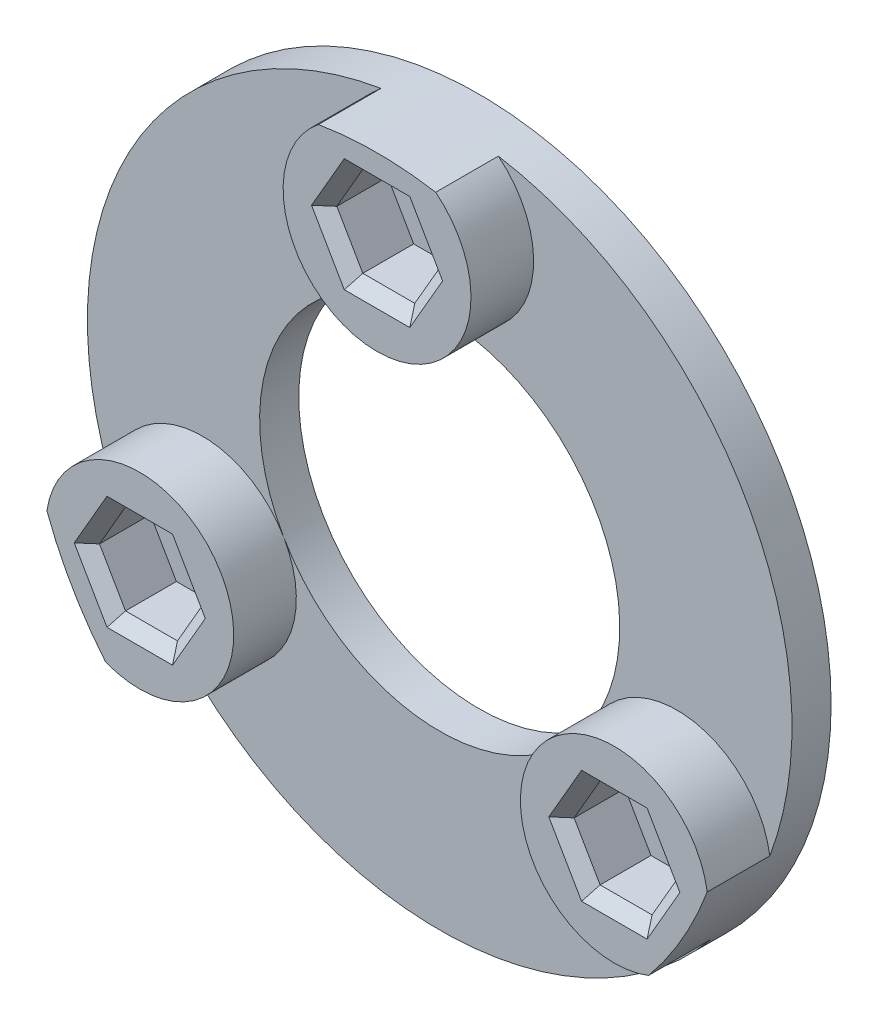
SolidWorks part; units mm, degrees
ref_plane "Front Plane" through (0, 0, 0) normal (0, 0, 1) x (1, 0, 0)
ref_plane "Top Plane" through (0, 0, 0) normal (0, 1, 0) x (1, 0, 0)
ref_plane "Right Plane" through (0, 0, 0) normal (1, 0, 0) x (0, 0, -1)
sketch "Sketch1" plane through (0, 0, 0) normal (0, 0, 1) x (1, 0, 0)
  circle A0 centre (0, 0) radius 22.5
  circle A1 centre (0, 0) radius 11.5
  circle A2 centre (0, 0) radius 17.5 construction
  circle A3 centre (0, 17.5) radius 1.65
  circle A4 centre (15.1554, -8.75) radius 1.65
  circle A6 centre (-15.1554, -8.75) radius 1.65
  point P8 (0, 0)
  point P13 (0, 0)
  dimension "D1" = 45
  dimension "D2" = 23
  dimension "D3" = 35
  dimension "D4" = 3.3
  dimension "D5" = 3
extrude "Boss-Extrude1" add sketch "Sketch1" along normal blind 2.5
sketch "Sketch2" plane through (0, 0, 2.5) normal (0, 0, 1) x (1, 0, 0)
  line L0 (1.375, 0) -> (-1.375, 0) construction
  line L1 (3.3198, 17.5) -> (1.6599, 20.375)
  line L2 (1.6599, 20.375) -> (-1.6599, 20.375)
  line L3 (-1.6599, 20.375) -> (-3.3198, 17.5)
  line L4 (-3.3198, 17.5) -> (-1.6599, 14.625)
  line L5 (-1.6599, 14.625) -> (1.6599, 14.625)
  line L6 (1.6599, 14.625) -> (3.3198, 17.5)
  line L7 (13.4956, -11.625) -> (16.8153, -11.625)
  line L8 (16.8153, -11.625) -> (18.4752, -8.75)
  line L9 (18.4752, -8.75) -> (16.8153, -5.875)
  line L10 (16.8153, -5.875) -> (13.4956, -5.875)
  line L11 (13.4956, -5.875) -> (11.8357, -8.75)
  line L12 (11.8357, -8.75) -> (13.4956, -11.625)
  line L13 (-16.8153, -5.875) -> (-18.4752, -8.75)
  line L14 (-18.4752, -8.75) -> (-16.8153, -11.625)
  line L15 (-16.8153, -11.625) -> (-13.4956, -11.625)
  line L16 (-13.4956, -11.625) -> (-11.8357, -8.75)
  line L17 (-11.8357, -8.75) -> (-13.4956, -5.875)
  line L18 (-13.4956, -5.875) -> (-16.8153, -5.875)
  arc A0 (-3.7475, 22.1857) -> (3.7475, 22.1857) centre (0, 17.5) ccw
  circle A1 centre (0, 17.5) radius 2.875 construction
  circle A2 centre (0, 0) radius 22.5 construction
  arc A3 (-3.7475, 22.1857) -> (3.7475, 22.1857) centre (0, 0) cw
  circle A4 centre (0, 17.5) radius 1.65
  arc A5 (21.0872, -7.8474) -> (17.3396, -14.3383) centre (0, 0) cw
  arc A6 (21.0872, -7.8474) -> (17.3396, -14.3383) centre (15.1554, -8.75) ccw
  arc A7 (-17.3396, -14.3383) -> (-21.0872, -7.8474) centre (0, 0) cw
  arc A8 (-17.3396, -14.3383) -> (-21.0872, -7.8474) centre (-15.1554, -8.75) ccw
  point P38 (0, 0)
  circle M11 centre (0, 0) radius 22.5
  dimension "D1" = 5.75
  dimension "D2" = 6
  dimension "D3" = 22.5
  dimension "D4" = 3.3
  dimension "D5" = 3
extrude "Boss-Extrude2" add sketch "Sketch2" along normal blind 4 contours A0 L6 L5 L4 L3 L2 L1 M11 | A8 L18 L17 L16 L15 L14 L13 M11 | A6 L12 L11 L10 L9 L8 L7 M11
chamfer "Chamfer1" distance 0.75 angle 45 18 edges at (15.1554, -11.625, 6.5) (17.6453, -10.1875, 6.5) (17.6453, -7.3125, 6.5) (15.1554, -5.875, 6.5) (12.6656, -7.3125, 6.5) (12.6656, -10.1875, 6.5) (-15.1554, -11.625, 6.5) (-12.6656, -10.1875, 6.5) (-12.6656, -7.3125, 6.5) (-15.1554, -5.875, 6.5) (-17.6453, -7.3125, 6.5) (-17.6453, -10.1875, 6.5) (-2.4898, 18.9375, 6.5) (-2.4898, 16.0625, 6.5) (0, 14.625, 6.5) (2.4898, 16.0625, 6.5) (2.4898, 18.9375, 6.5) (0, 20.375, 6.5)
